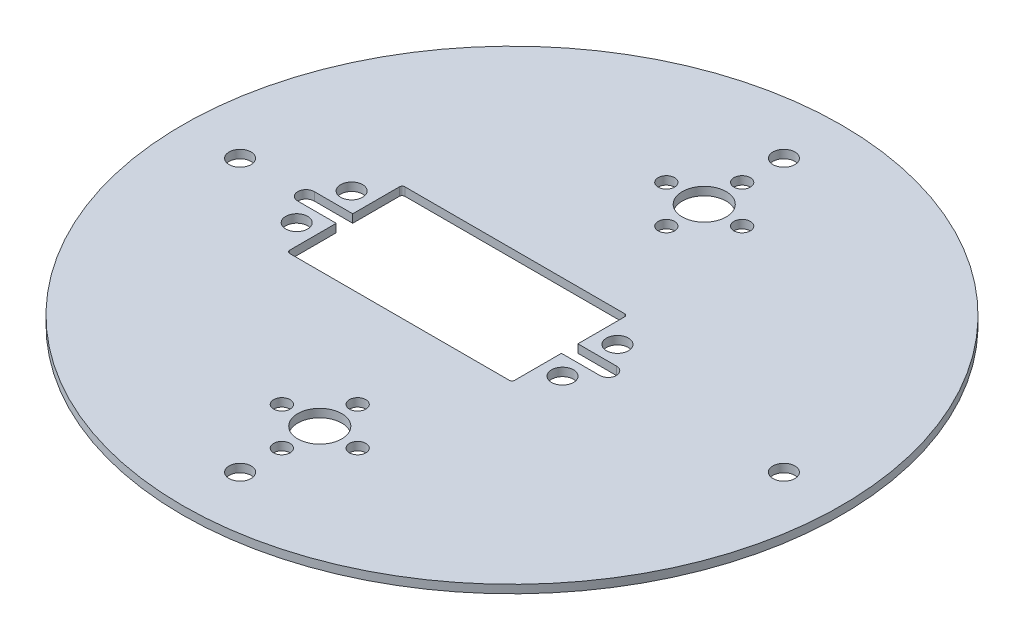
SolidWorks part; units mm, degrees
ref_plane "Front Plane" through (0, 0, 0) normal (0, 0, 1) x (1, 0, 0)
ref_plane "Top Plane" through (0, 0, 0) normal (0, 1, 0) x (1, 0, 0)
ref_plane "Right Plane" through (0, 0, 0) normal (1, 0, 0) x (0, 0, -1)
sketch "Sketch1" plane through (0, 0, 0) normal (0, 1, 0) x (1, 0, 0)
  line L0 (0, 60) -> (0, -60) construction
  line L1 (-60, 0) -> (60, 0) construction
  line L2 (0, 35) -> (0, 41.9) construction
  line L3 (0, 60) -> (0, 10.5) construction
  line L4 (0, -60) -> (0, -10.5) construction
  line L5 (-60, 0) -> (-37.5, 0) construction
  line L6 (-37.5, -1.5) -> (-30.5, -1.5)
  line L7 (-37.5, 1.5) -> (-30.5, 1.5)
  line L8 (-30.5, 1.5) -> (-30.5, 5) construction
  line L9 (-30.5, 1.5) -> (-30.5, 10.5) construction
  line L10 (-30.5, 1.5) -> (-30.5, 10)
  line L11 (-30, 10.5) -> (10, 10.5)
  line L12 (10.5, 10) -> (10.5, 1.5)
  line L13 (10.5, 1.5) -> (17.5, 1.5)
  line L14 (17.5, 0) -> (17.5, 1.5) construction
  line L15 (17.5, -1.5) -> (10.5, -1.5)
  line L16 (10.5, -1.5) -> (10.5, -10)
  line L17 (10, -10.5) -> (-30, -10.5)
  line L18 (-30.5, -10) -> (-30.5, -1.5)
  line L19 (-30.5, 5) -> (-34.2, 5) construction
  line L20 (-10, -10.5) -> (-10, 10.5) construction
  circle A0 centre (0, 0) radius 60
  circle A1 centre (0, 0) radius 49.5 construction
  circle A2 centre (0, 49.5) radius 2
  circle A3 centre (-49.5, 0) radius 2
  circle A4 centre (0, -49.5) radius 2
  circle A5 centre (49.5, 0) radius 2
  circle A6 centre (0, 0) radius 35 construction
  circle A7 centre (0, 35) radius 4
  circle A8 centre (0, 41.9) radius 1.5
  circle A9 centre (6.9, 35) radius 1.5
  circle A10 centre (0, 28.1) radius 1.5
  circle A11 centre (-6.9, 35) radius 1.5
  circle A12 centre (0, -35) radius 4
  circle A13 centre (0, -28.1) radius 1.5
  circle A14 centre (-6.9, -35) radius 1.5
  circle A15 centre (0, -41.9) radius 1.5
  circle A16 centre (6.9, -35) radius 1.5
  arc A17 (-37.5, 1.5) -> (-37.5, -1.5) centre (-37.5, 0) ccw
  arc A18 (17.5, -1.5) -> (17.5, 1.5) centre (17.5, 0) ccw
  circle A19 centre (-34.2, 5) radius 2
  circle A20 centre (-34.2, -5) radius 2
  circle A21 centre (14.2, 5) radius 2
  circle A22 centre (14.2, -5) radius 2
  arc A23 (-30, -10.5) -> (-30.5, -10) centre (-30, -10) cw
  arc A24 (10.5, -10) -> (10, -10.5) centre (10, -10) cw
  arc A25 (10, 10.5) -> (10.5, 10) centre (10, 10) cw
  arc A26 (-30.5, 10) -> (-30, 10.5) centre (-30, 10) cw
  point P30 (0, 35)
  dimension "D1" = 4
  dimension "D2" = 0.5
extrude "Boss-Extrude1" add sketch "Sketch1" along normal blind 1.5
